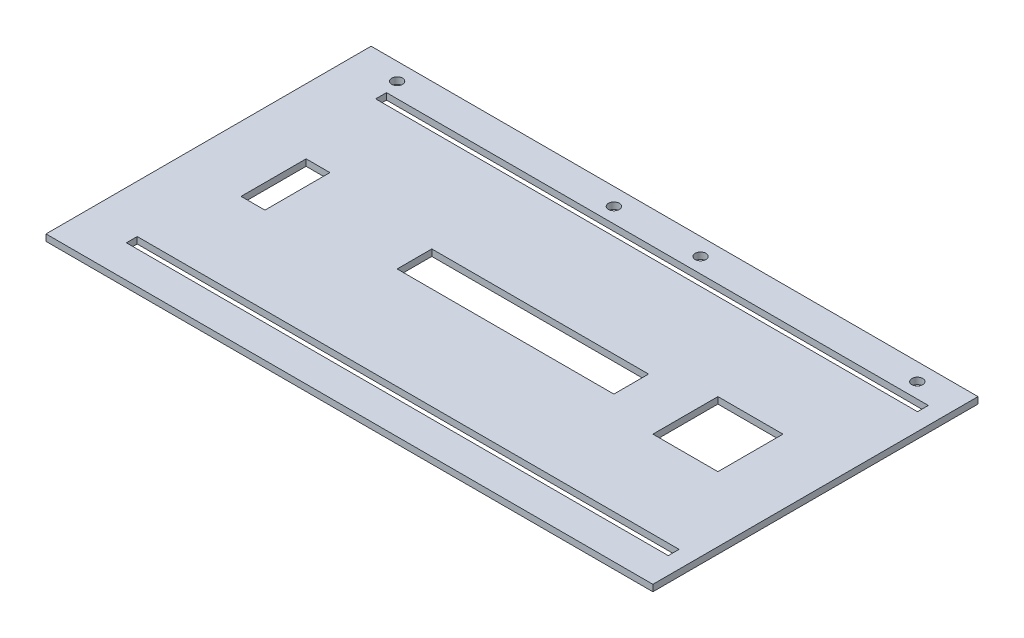
SolidWorks part; units mm, degrees
ref_plane "前视基准面" through (0, 0, 0) normal (0, 0, 1) x (1, 0, 0)
ref_plane "上视基准面" through (0, 0, 0) normal (0, 1, 0) x (1, 0, 0)
ref_plane "右视基准面" through (0, 0, 0) normal (1, 0, 0) x (0, 0, -1)
other "Configuration Table"
sketch "草图1" plane through (0, 0, 0) normal (0, 1, 0) x (1, 0, 0)
  line L1 (-70.1772, 39.3359) -> (209.8228, 39.3359)
  line L2 (-70.1772, 39.3359) -> (-70.1772, -110.6641)
  line L3 (-70.1772, -110.6641) -> (209.8228, -110.6641)
  line L4 (209.8228, 39.3359) -> (209.8228, -110.6641)
  dimension "D1" = 150
  dimension "D2" = 280
extrude "凸台-拉伸1" add sketch "草图1" along normal blind 3
sketch "草图2" plane through (0, 3, 0) normal (0, 1, 0) x (1, 0, 0)
  line L4 (24.8228, -43.6641) -> (124.8228, -43.6641)
  line L5 (24.8228, -43.6641) -> (24.8228, -27.6641)
  line L6 (24.8228, -27.6641) -> (124.8228, -27.6641)
  line L7 (124.8228, -43.6641) -> (124.8228, -27.6641)
  point P9 (74.8228, -35.6641)
  dimension "D1" = 16
  dimension "D2" = 100
extrude "切除-拉伸1" cut sketch "草图2" against normal blind 3
sketch "草图3" plane through (0, 0, 0) normal (0, -1, 0) x (1, 0, 0)
  line L1 (-48.0896, 95.6641) -> (201.9104, 95.6641)
  line L2 (-48.0896, 95.6641) -> (-48.0896, 90.6641)
  line L3 (-48.0896, 90.6641) -> (201.9104, 90.6641)
  line L4 (201.9104, 95.6641) -> (201.9104, 90.6641)
  line L5 (-48.0896, -19.3359) -> (201.9104, -19.3359)
  line L6 (-48.0896, -19.3359) -> (-48.0896, -24.3359)
  line L7 (-48.0896, -24.3359) -> (201.9104, -24.3359)
  line L8 (201.9104, -19.3359) -> (201.9104, -24.3359)
  line L13 (-70.1772, 110.6641) -> (209.8228, 110.6641) construction
  line L14 (209.8228, -39.3359) -> (-70.1772, -39.3359) construction
  dimension "D1" = 5
  dimension "D2" = 250
  dimension "D3" = 5
  dimension "D4" = 250
  dimension "D5" = 15
  dimension "D6" = 15
extrude "切除-拉伸2" cut sketch "草图3" against normal blind 3
sketch "草图4" plane through (0, 3, 0) normal (0, 1, 0) x (1, 0, 0)
  line L0 (-70.1772, 39.3359) -> (-70.1772, -110.6641) construction
  line L1 (209.8228, 39.3359) -> (-70.1772, 39.3359) construction
  line L2 (209.8228, -110.6641) -> (209.8228, 39.3359) construction
  circle A0 centre (-50.1772, 31.3359) radius 2.5
  circle A1 centre (49.8228, 31.3359) radius 2.5
  circle A2 centre (189.8228, 31.3359) radius 2.5
  circle A3 centre (89.8228, 31.3359) radius 2.5
  dimension "D1" = 20
  dimension "D2" = 8
  dimension "D3" = 120
  dimension "D4" = 20
  dimension "D5" = 8
  dimension "D6" = 120
extrude "切除-拉伸3" cut sketch "草图4" against normal blind 3
sketch "草图5" plane through (0, 0, 0) normal (0, -1, 0) x (1, 0, 0)
  line L0 (209.8228, 110.6641) -> (209.8228, -39.3359) construction
  line L1 (149.8228, 50.6641) -> (179.8228, 50.6641)
  line L2 (149.8228, 50.6641) -> (149.8228, 20.6641)
  line L3 (149.8228, 20.6641) -> (179.8228, 20.6641)
  line L4 (179.8228, 50.6641) -> (179.8228, 20.6641)
  line L5 (209.8228, -39.3359) -> (-70.1772, -39.3359) construction
  line L6 (-70.1772, -39.3359) -> (-70.1772, 110.6641) construction
  line L7 (-29.1772, 50.6641) -> (-40.1772, 50.6641)
  line L8 (-29.1772, 50.6641) -> (-29.1772, 20.6641)
  line L9 (-29.1772, 20.6641) -> (-40.1772, 20.6641)
  line L10 (-40.1772, 50.6641) -> (-40.1772, 20.6641)
  line L11 (209.8228, -39.3359) -> (-70.1772, -39.3359) construction
  dimension "D1" = 30
  dimension "D2" = 30
  dimension "D3" = 30
  dimension "D4" = 60
  dimension "D5" = 30
  dimension "D6" = 11
  dimension "D7" = 30
  dimension "D8" = 60
extrude "切除-拉伸4" cut sketch "草图5" against normal blind 3
